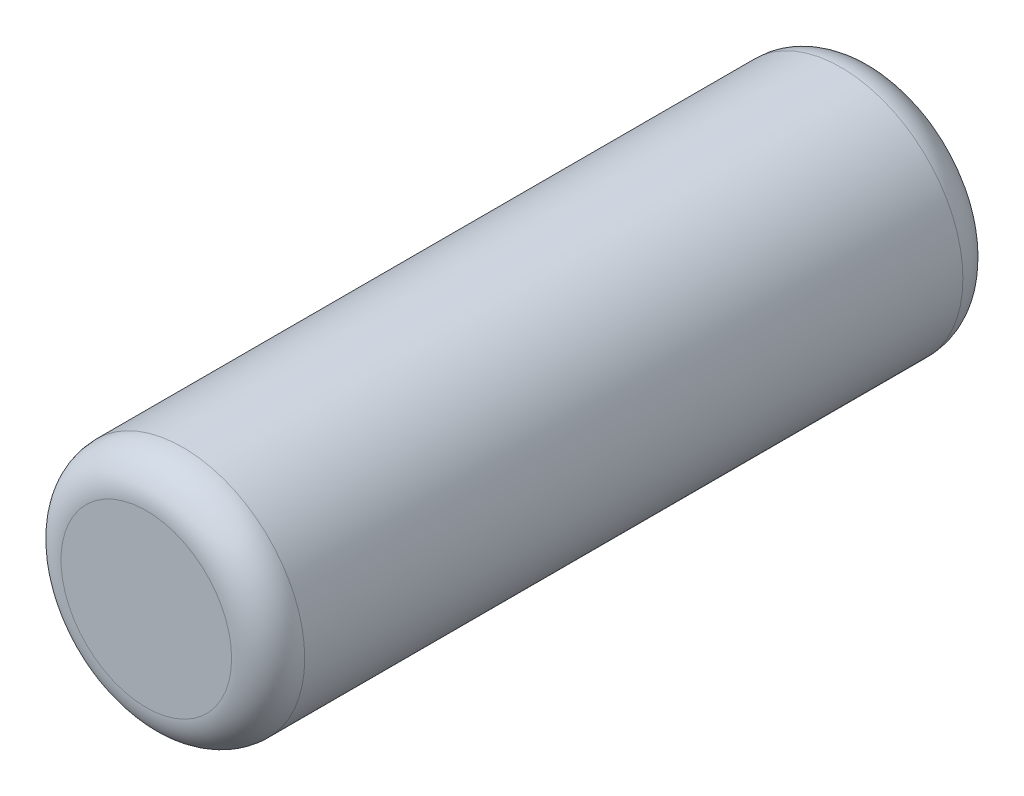
SolidWorks part; units mm, degrees
material "45"
ref_plane "前视基准面" through (0, 0, 0) normal (0, 0, 1) x (1, 0, 0)
ref_plane "上视基准面" through (0, 0, 0) normal (0, 1, 0) x (1, 0, 0)
ref_plane "右视基准面" through (0, 0, 0) normal (1, 0, 0) x (0, 0, -1)
sketch "草图1" plane through (0, 0, 0) normal (0, 0, 1) x (1, 0, 0)
  circle A0 centre (0, 0) radius 1
  dimension "D1" = 2
extrude "拉伸1" add sketch "草图1" along normal mid plane 6
chamfer "倒角1" [suppressed] distance 0.2 angle 45
fillet "圆角1" radius 0.3 1 edges at (1, 0, 3)
fillet "圆角2" radius 0.3 1 edges at (1, 0, -3)
